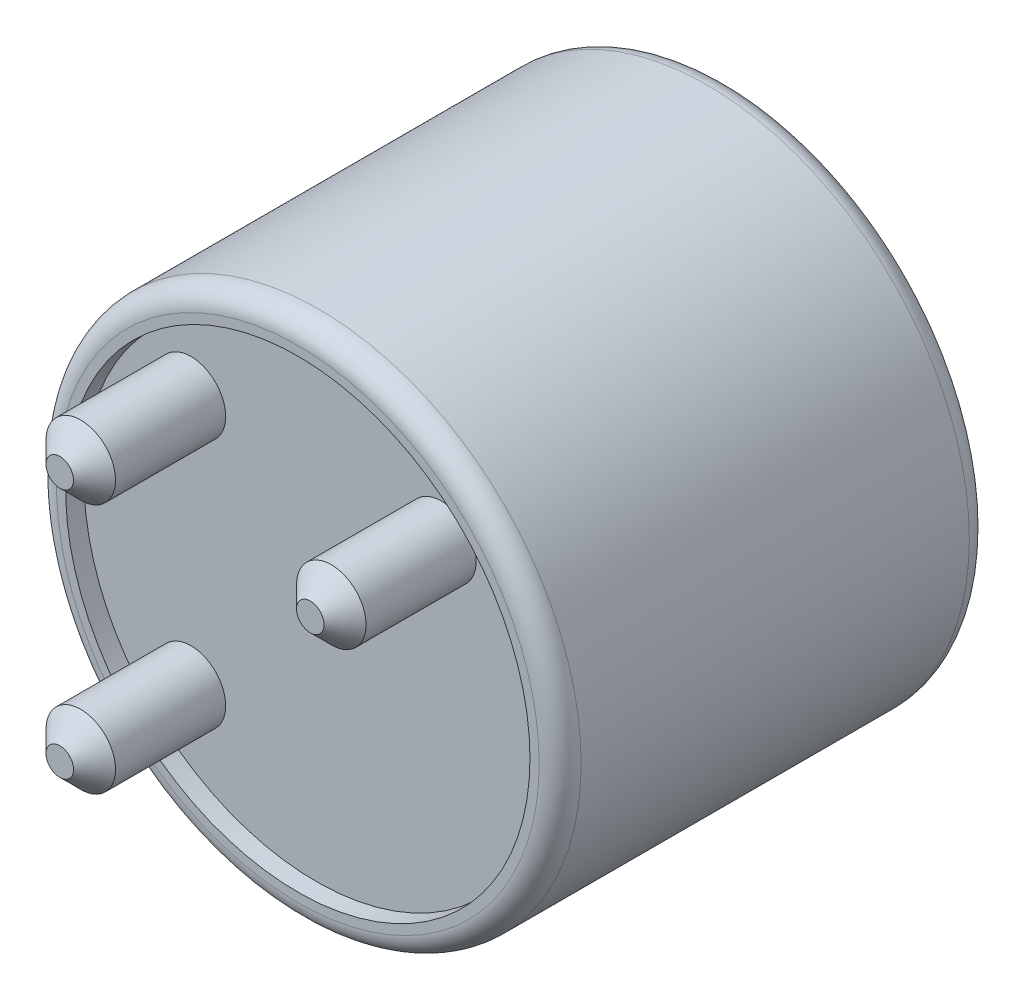
SolidWorks part; units mm, degrees
ref_plane "Спереди" through (0, 0, 0) normal (0, 0, 1) x (1, 0, 0)
ref_plane "Сверху" through (0, 0, 0) normal (0, 1, 0) x (1, 0, 0)
ref_plane "Справа" through (0, 0, 0) normal (1, 0, 0) x (0, 0, -1)
sketch "Эскиз1" plane through (0, 0, 0) normal (0, 0, 1) x (1, 0, 0)
  circle A0 centre (0, 0) radius 10
  dimension "D1" = 20
extrude "Бобышка-Вытянуть1" add sketch "Эскиз1" along normal blind 16.4
sketch "Эскиз2" plane through (0, 0, 16.4) normal (0, 0, 1) x (1, 0, 0)
  circle A0 centre (0, 0) radius 8.85
  dimension "D1" = 17.7
extrude "Вырез-Вытянуть1" cut sketch "Эскиз2" against normal blind 0.7
sketch "Эскиз3" plane through (0, 0, 15.7) normal (0, 0, 1) x (1, 0, 0)
  line L1 (4.775, -4.775) -> (-4.775, -4.775) construction
  line L2 (4.775, -4.775) -> (4.775, 4.775) construction
  line L3 (4.775, 4.775) -> (-4.775, 4.775) construction
  line L4 (-4.775, -4.775) -> (-4.775, 4.775) construction
  line L5 (4.775, -4.775) -> (-4.775, 4.775) construction
  line L6 (4.775, 4.775) -> (-4.775, -4.775) construction
  circle A0 centre (-4.775, 4.775) radius 1.325
  circle A1 centre (-4.775, -4.775) radius 1.325
  circle A2 centre (4.775, 4.775) radius 1.325
  point P0 (0, 0)
  dimension "D3" = 2.65
  dimension "D1" = 9.55
  dimension "D2" = 9.55
extrude "Бобышка-Вытянуть2" add sketch "Эскиз3" along normal blind 5
chamfer "Фаска1" distance 0.8 angle 45 3 edges at (6.1, 4.775, 20.7) (-3.45, -4.775, 20.7) (-3.45, 4.775, 20.7)
sketch "Эскиз4" plane through (0, 0, 0) normal (0, 0, -1) x (-1, 0, 0)
  circle A0 centre (0, 0) radius 8.05
  dimension "D1" = 16.1
extrude "Вырез-Вытянуть2" cut sketch "Эскиз4" against normal blind 1.5
sketch "Эскиз5" plane through (0, 0, 1.5) normal (0, 0, -1) x (-1, 0, 0)
  circle A0 centre (0, 0) radius 0.6
  dimension "D1" = 1.2
extrude "Вырез-Вытянуть3" cut sketch "Эскиз5" against normal blind 3
fillet "Скругление1" radius 0.8 2 edges at (10, 0, 0) (10, 0, 16.4)
